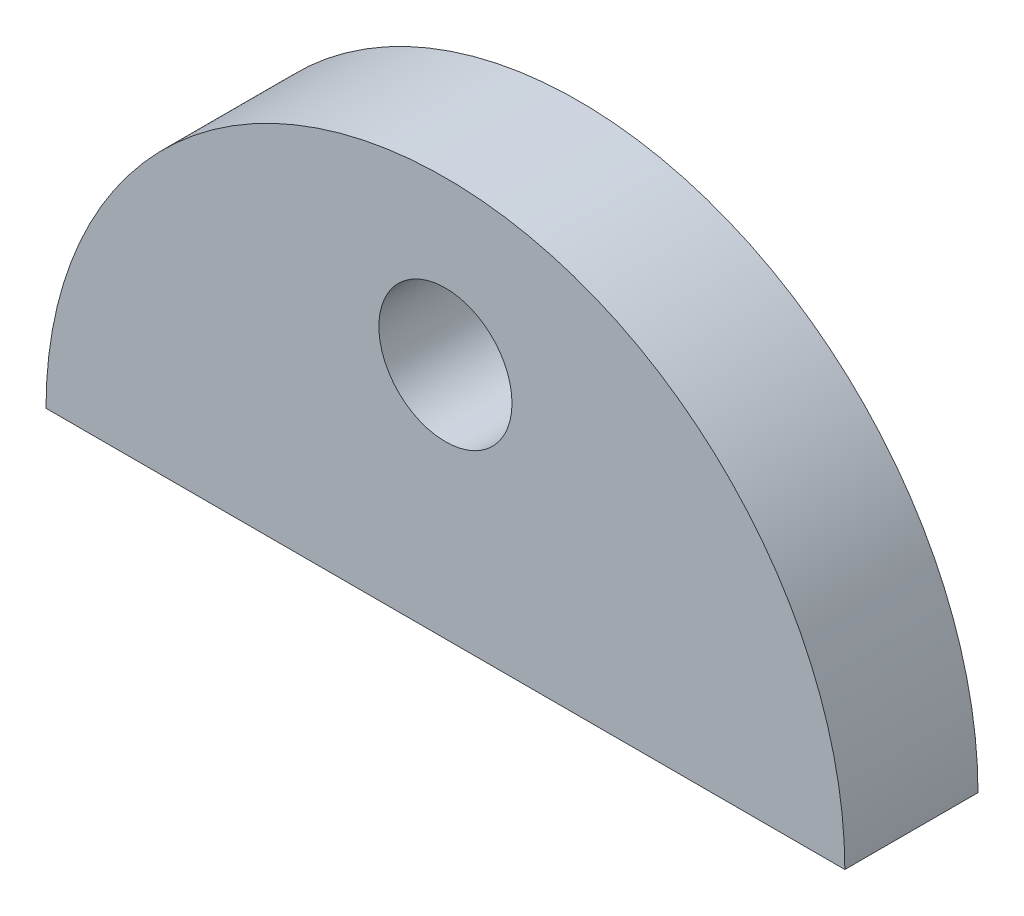
SolidWorks part; units mm, degrees
ref_plane "Front Plane" through (0, 0, 0) normal (0, 0, 1) x (1, 0, 0)
ref_plane "Top Plane" through (0, 0, 0) normal (0, 1, 0) x (1, 0, 0)
ref_plane "Right Plane" through (0, 0, 0) normal (1, 0, 0) x (0, 0, -1)
sketch "Sketch2" plane through (0, 0, 0) normal (0, 0, 1) x (1, 0, 0)
  line L0 (-38.1, 0) -> (0, 0)
  arc A0 (-38.1, 0) -> (0, 0) centre (-19.05, 0) cw
  circle A1 centre (-19.05, 11.3201) radius 3.175
  dimension "D1" = 38.1
  dimension "D2" = 6.35
extrude "Boss-Extrude1" add sketch "Sketch2" along normal blind 6.35
scale "Scale1" scale about centroid uniform scaling yes scale factor 1.5
scale "Scale2" scale about centroid uniform scaling yes scale factor 0.67
scale "Scale3" scale about centroid uniform scaling yes scale factor 2
